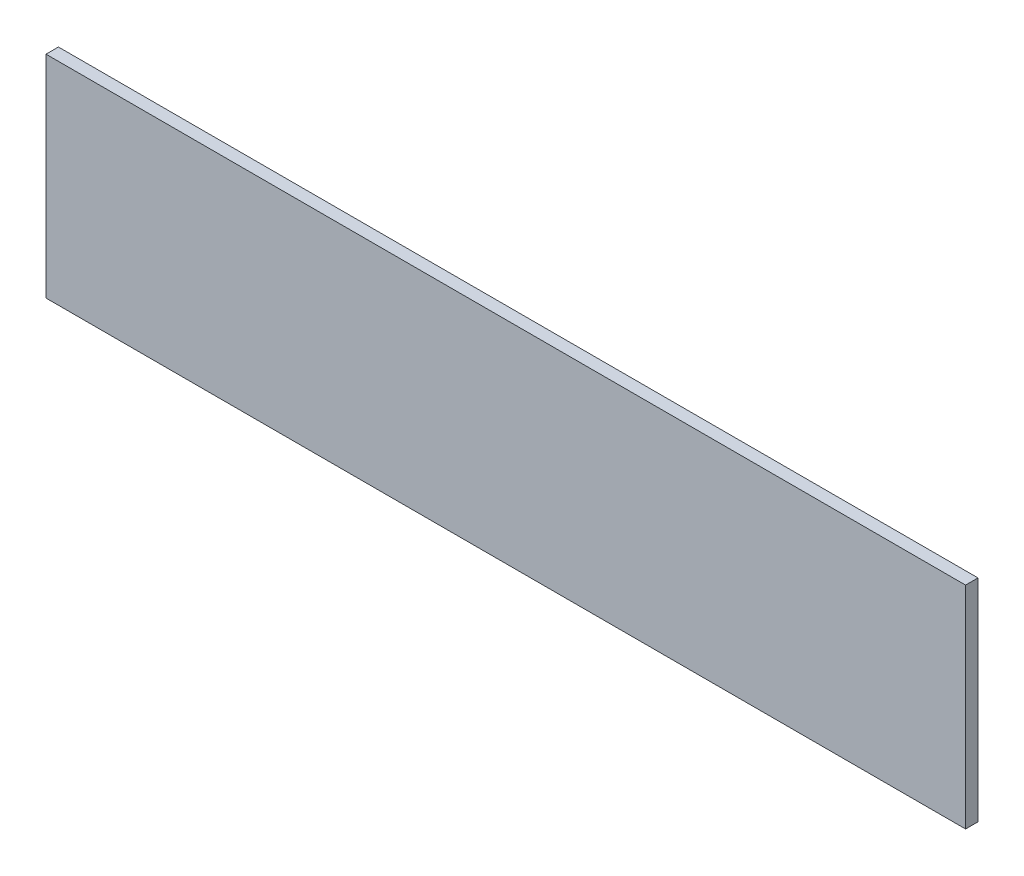
SolidWorks part; units mm, degrees
material "6061 Alloy"
ref_plane "Front Plane" through (0, 0, 0) normal (0, 0, 1) x (1, 0, 0)
ref_plane "Top Plane" through (0, 0, 0) normal (0, 1, 0) x (1, 0, 0)
ref_plane "Right Plane" through (0, 0, 0) normal (1, 0, 0) x (0, 0, -1)
sketch "Sketch1" plane through (0, 0, 0) normal (0, 0, 1) x (1, 0, 0)
  line L1 (-234.95, 6.2266) -> (0, 6.2266)
  line L2 (-234.95, 6.2266) -> (-234.95, 60.2016)
  line L3 (-234.95, 60.2016) -> (0, 60.2016)
  line L4 (0, 6.2266) -> (0, 60.2016)
  dimension "D1" = 234.95
  dimension "D2" = 53.975
extrude "Boss-Extrude2" add sketch "Sketch1" along normal blind 3.175
